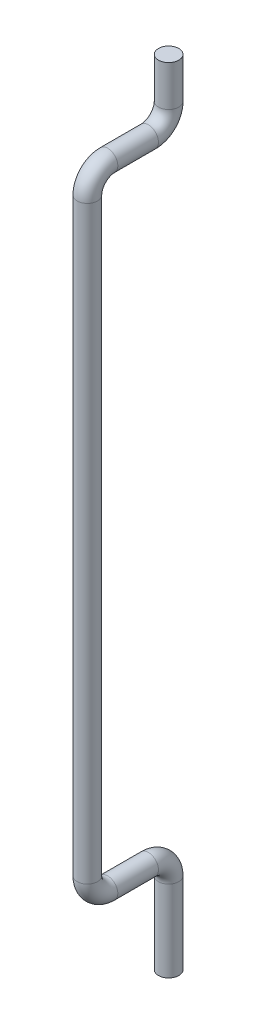
SolidWorks part; units mm, degrees
ref_plane "Front Plane" through (0, 0, 0) normal (0, 0, 1) x (1, 0, 0)
ref_plane "Top Plane" through (0, 0, 0) normal (0, 1, 0) x (1, 0, 0)
ref_plane "Right Plane" through (0, 0, 0) normal (1, 0, 0) x (0, 0, -1)
sketch "Sketch1" plane through (0, 0, 0) normal (1, 0, 0) x (0, 0, -1)
  line L0 (10.22, 3) -> (12.22, 3)
  line L1 (13.22, 2) -> (13.22, -2)
  line L2 (9.22, 4) -> (9.22, 33)
  line L3 (10.22, 34) -> (12.22, 34)
  line L4 (13.22, 35) -> (13.22, 37)
  arc A0 (12.22, 3) -> (13.22, 2) centre (12.22, 2) cw
  arc A1 (9.22, 4) -> (10.22, 3) centre (10.22, 4) ccw
  arc A3 (9.22, 33) -> (10.22, 34) centre (10.22, 33) cw
  arc A4 (12.22, 34) -> (13.22, 35) centre (12.22, 35) ccw
  point P9 (13.22, 3)
  point P19 (9.22, 34)
  point P22 (13.22, 34)
  dimension "D8" = 1
  dimension "D9" = 1
  dimension "D5" = 1
  dimension "D1" = 3
  dimension "D2" = 4
  dimension "D3" = 31
  dimension "D4" = 5
ref_plane "Plane1" through (0, -2, 0) normal (0, 1, 0) x (1, 0, 0)
sketch "Sketch2" plane through (0, -2, 0) normal (0, 1, 0) x (1, 0, 0)
  circle A0 centre (0, 13.22) radius 0.5
  dimension "D1" = 1
sweep "Sweep1" add profiles "Sketch2" path "Sketch1"
